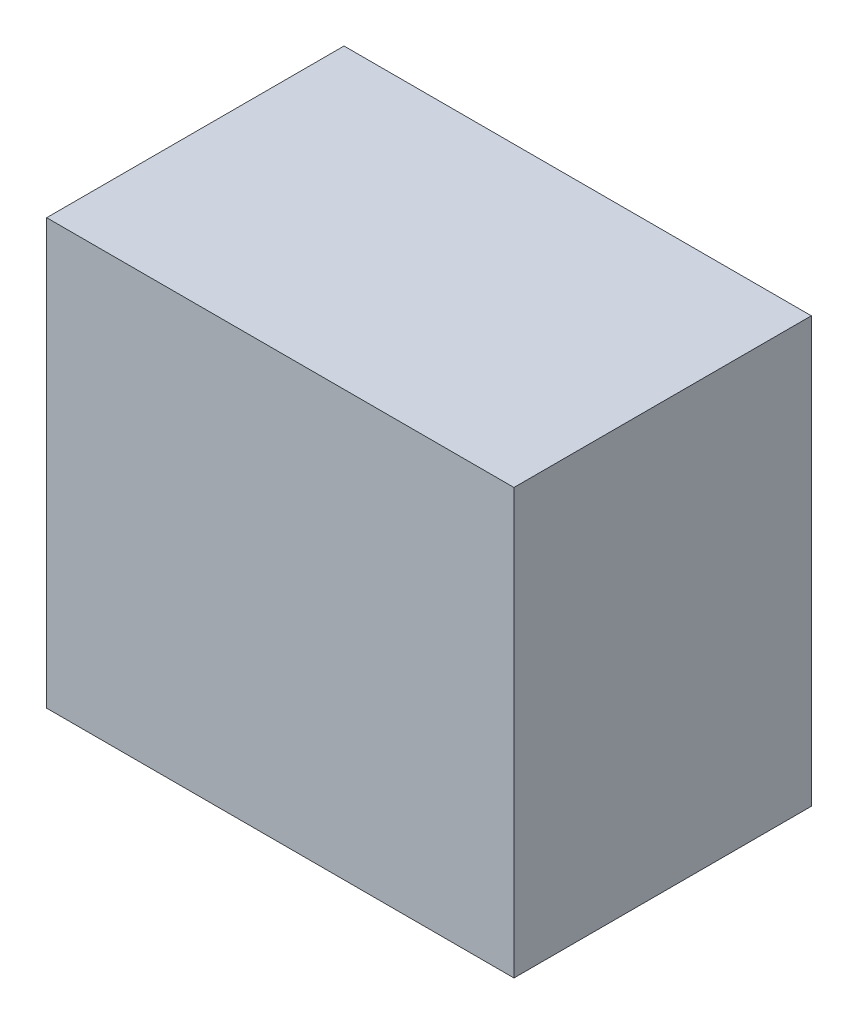
SolidWorks part; units mm, degrees
ref_plane "Alzado" through (0, 0, 0) normal (0, 0, 1) x (1, 0, 0)
ref_plane "Planta" through (0, 0, 0) normal (0, 1, 0) x (1, 0, 0)
ref_plane "Vista lateral" through (0, 0, 0) normal (1, 0, 0) x (0, 0, -1)
sketch "Croquis1" plane through (0, 0, 0) normal (0, 0, 1) x (1, 0, 0)
  line L1 (0, 0) -> (550, 0)
  line L2 (0, 0) -> (0, 500)
  line L3 (0, 500) -> (550, 500)
  line L4 (550, 0) -> (550, 500)
  dimension "D1" = 550
  dimension "D2" = 500
extrude "Saliente-Extruir1" add sketch "Croquis1" along normal blind 350
